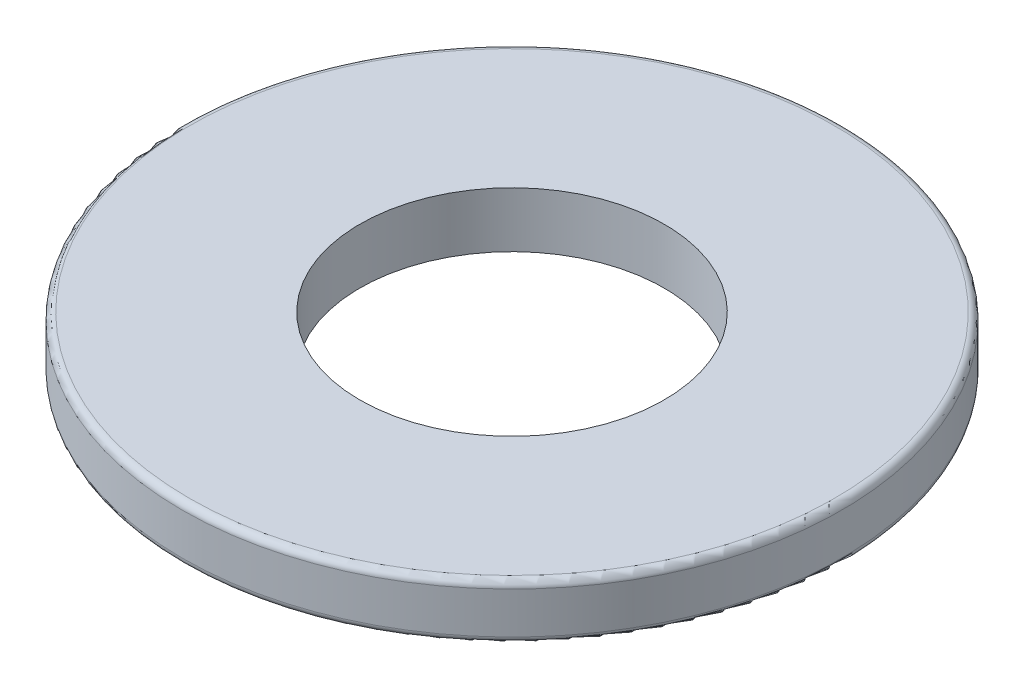
SolidWorks part; units mm, degrees
material "201 Aço inoxidável recozido (SS)"
ref_plane "Plano frontal" through (0, 0, 0) normal (0, 0, 1) x (1, 0, 0)
ref_plane "Plano superior" through (0, 0, 0) normal (0, 1, 0) x (1, 0, 0)
ref_plane "Plano direito" through (0, 0, 0) normal (1, 0, 0) x (0, 0, -1)
sketch "Esboço1" plane through (0, 0, 0) normal (0, 1, 0) x (1, 0, 0)
  circle A0 centre (0, 0) radius 4.7625
  circle A1 centre (0, 0) radius 2.2
  dimension "D1" = 4.4
  dimension "D2" = 9.525
extrude "Ressalto-extrusão1" add sketch "Esboço1" along normal blind 0.8
fillet "Filete1" radius 0.1 2 edges at (0, 0.8, 4.7625) (0, 0, 4.7625)
